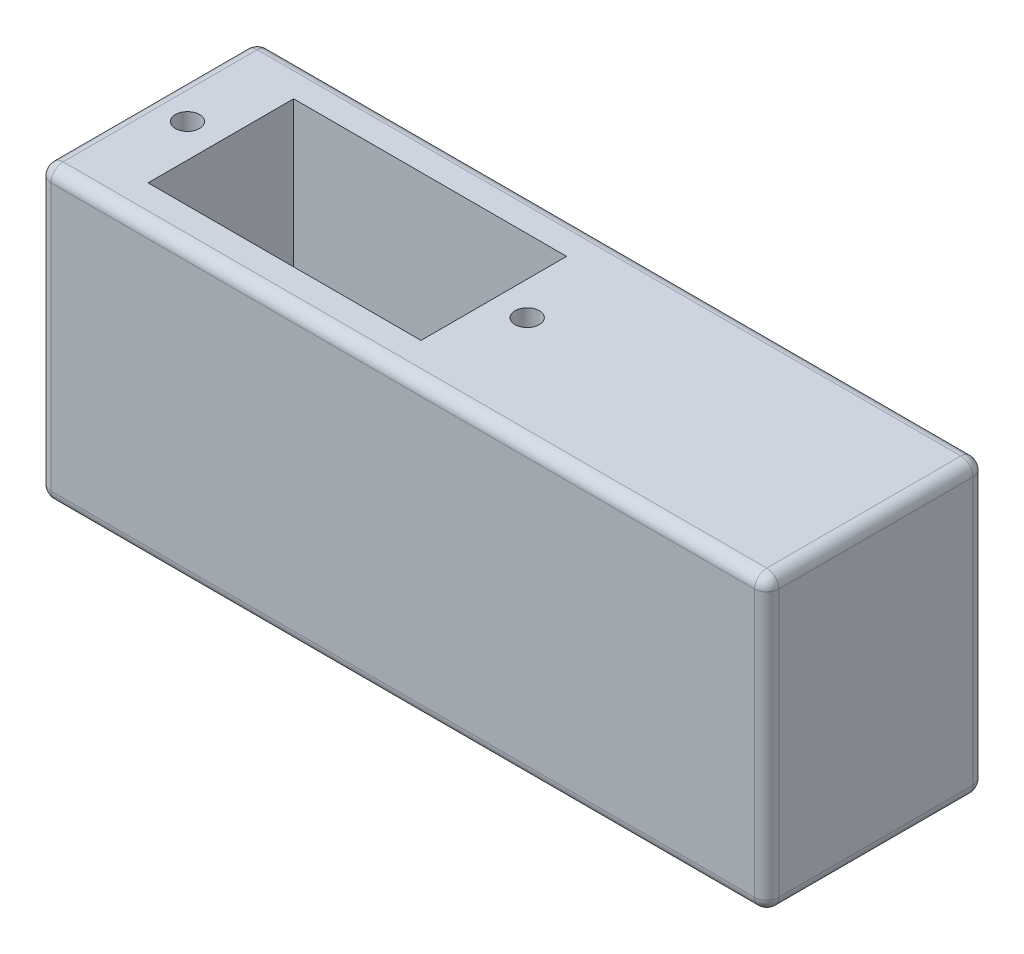
SolidWorks part; units mm, degrees
material "ABS"
ref_plane "前视基准面" through (0, 0, 0) normal (0, 0, 1) x (1, 0, 0)
ref_plane "上视基准面" through (0, 0, 0) normal (0, 1, 0) x (1, 0, 0)
ref_plane "右视基准面" through (0, 0, 0) normal (1, 0, 0) x (0, 0, -1)
sketch "草图1" plane through (0, 0, 0) normal (0, 1, 0) x (1, 0, 0)
  line L1 (-30, -9) -> (30, -9)
  line L2 (-30, -9) -> (-30, 9)
  line L3 (-30, 9) -> (30, 9)
  line L4 (30, -9) -> (30, 9)
  line L5 (-30, -9) -> (30, 9) construction
  line L6 (-30, 9) -> (30, -9) construction
  line L7 (-24, -6) -> (-1.5, -6)
  line L8 (-24, -6) -> (-24, 6)
  line L9 (-24, 6) -> (-1.5, 6)
  line L10 (-1.5, -6) -> (-1.5, 6)
  point P0 (0, 0)
  dimension "D1" = 12
  dimension "D2" = 22.5
  dimension "D3" = 3
  dimension "D4" = 6
  dimension "D5" = 3
  dimension "D6" = 60
extrude "凸台-拉伸1" add sketch "草图1" along normal blind 21
sketch "草图2" plane through (0, 0, 0) normal (0, -1, 0) x (1, 0, 0)
  line L1 (-30, 9) -> (30, 9)
  line L2 (-30, 9) -> (-30, -9)
  line L3 (-30, -9) -> (30, -9)
  line L4 (30, 9) -> (30, -9)
extrude "凸台-拉伸2" add sketch "草图2" along normal blind 3
sketch "草图3" plane through (-30, 0, 0) normal (-1, 0, 0) x (0, 0, 1)
  line L1 (-3, 0) -> (3, 0)
  line L2 (-3, 0) -> (-3, 3)
  line L3 (-3, 3) -> (3, 3)
  line L4 (3, 0) -> (3, 3)
  point P5 (0, 0)
  dimension "D1" = 3
  dimension "D2" = 6
extrude "切除-拉伸1" cut sketch "草图3" against normal blind 6
sketch "草图4" plane through (0, -3, 0) normal (0, -1, 0) x (1, 0, 0)
  line L0 (-30, 3) -> (-30, -3) construction
  circle A0 centre (-18, 0) radius 2.75
  dimension "D1" = 5.5
  dimension "D2" = 12
extrude "凸台-拉伸3" add sketch "草图4" along normal blind 5
sketch "草图6" plane through (0, 21, 0) normal (0, 1, 0) x (1, 0, 0)
  line L0 (-12.75, 6) -> (-12.75, -0.7331) construction
  line L1 (-1.5, 6) -> (-24, 6) construction
  circle A0 centre (-26.75, 0) radius 1
  circle A1 centre (1.25, 0) radius 1
  dimension "D1" = 2
  dimension "D2" = 14
extrude "切除-拉伸2" cut sketch "草图6" against normal blind 5
fillet "圆角1" radius 1 17 edges at (30, 21, 0) (30, -3, 0) (-18, -3, -2.75) (0, 21, 9) (30, 9, 9) (0, -3, 9) (-30, 21, 0) (-30, 9, 9) (-30, -3, 0) (-30, 1.5, 3) (-30, 3, 0) (-30, 1.5, -3) (-30, 0, 0) (0, 21, -9) (-30, 9, -9) (0, -3, -9) (30, 9, -9)
